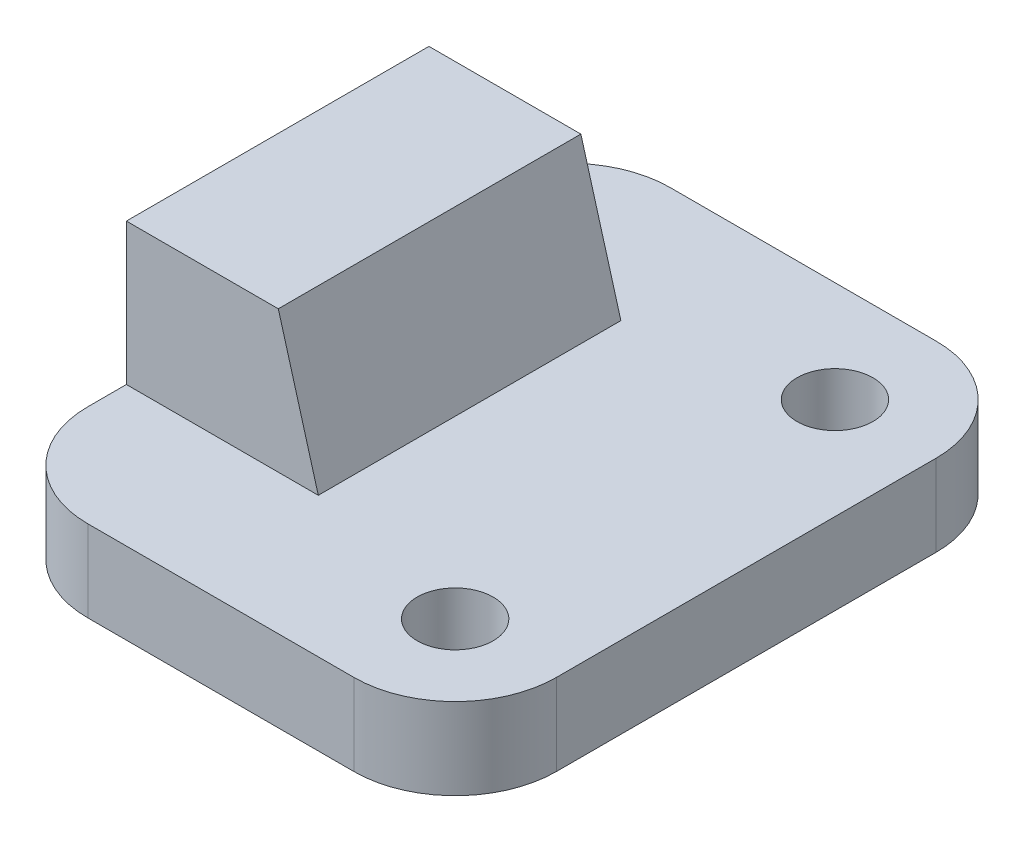
SolidWorks part; units mm, degrees
ref_plane "Front Plane" through (0, 0, 0) normal (0, 0, 1) x (1, 0, 0)
ref_plane "Top Plane" through (0, 0, 0) normal (0, 1, 0) x (1, 0, 0)
ref_plane "Right Plane" through (0, 0, 0) normal (1, 0, 0) x (0, 0, -1)
sketch "Sketch1" plane through (0, 0, 0) normal (0, 1, 0) x (1, 0, 0)
  line L0 (4, 0) -> (14.51, 0)
  line L1 (18.51, 4) -> (18.51, 19)
  line L2 (14.51, 23) -> (4, 23)
  line L3 (0, 19) -> (0, 4)
  arc A0 (4, 23) -> (0, 19) centre (4, 19) ccw
  arc A1 (4, 0) -> (0, 4) centre (4, 4) cw
  arc A2 (14.51, 0) -> (18.51, 4) centre (14.51, 4) ccw
  arc A3 (18.51, 19) -> (14.51, 23) centre (14.51, 19) ccw
  circle A4 centre (14.51, 19) radius 1.5
  circle A5 centre (14.51, 4) radius 1.5
  point P9 (0, 0)
  dimension "D3" = 4
  dimension "D4" = 4
  dimension "D5" = 4
  dimension "D6" = 4
  dimension "D8" = 3
  dimension "D9" = 3
  dimension "D1" = 23
  dimension "D2" = 18.51
  dimension "D7" = 15
extrude "Boss-Extrude1" add sketch "Sketch1" along normal blind 3.22
sketch "Sketch3" plane through (0, 3.22, 0) normal (0, 1, 0) x (1, 0, 0)
  line L0 (0, 17.475) -> (0, 5.525)
  line L1 (0, 19) -> (0, 4) construction
  line L2 (0, 5.525) -> (6, 5.525)
  line L3 (6, 5.525) -> (6, 17.475)
  line L4 (6, 17.475) -> (0, 17.475)
  line L5 (14.51, 23) -> (4, 23) construction
  point P8 (0, 11.5)
  dimension "D1" = 11.5
  dimension "D2" = 11.95
  dimension "D3" = 6
extrude "Boss-Extrude2" add sketch "Sketch3" along normal blind 5.59
sketch "Sketch4" plane through (0, 0, -5.525) normal (0, 0, 1) x (1, 0, 0)
  line L0 (0, 3.22) -> (7.58, 3.22)
  line L1 (4, 3.22) -> (14.51, 3.22) construction
  line L2 (7.58, 3.22) -> (6, 8.81)
  line L3 (6, 8.81) -> (0, 8.81)
  line L4 (0, 8.81) -> (0, 3.22)
  dimension "D1" = 7.58
extrude "Boss-Extrude3" add sketch "Sketch4" against normal blind 11.95
